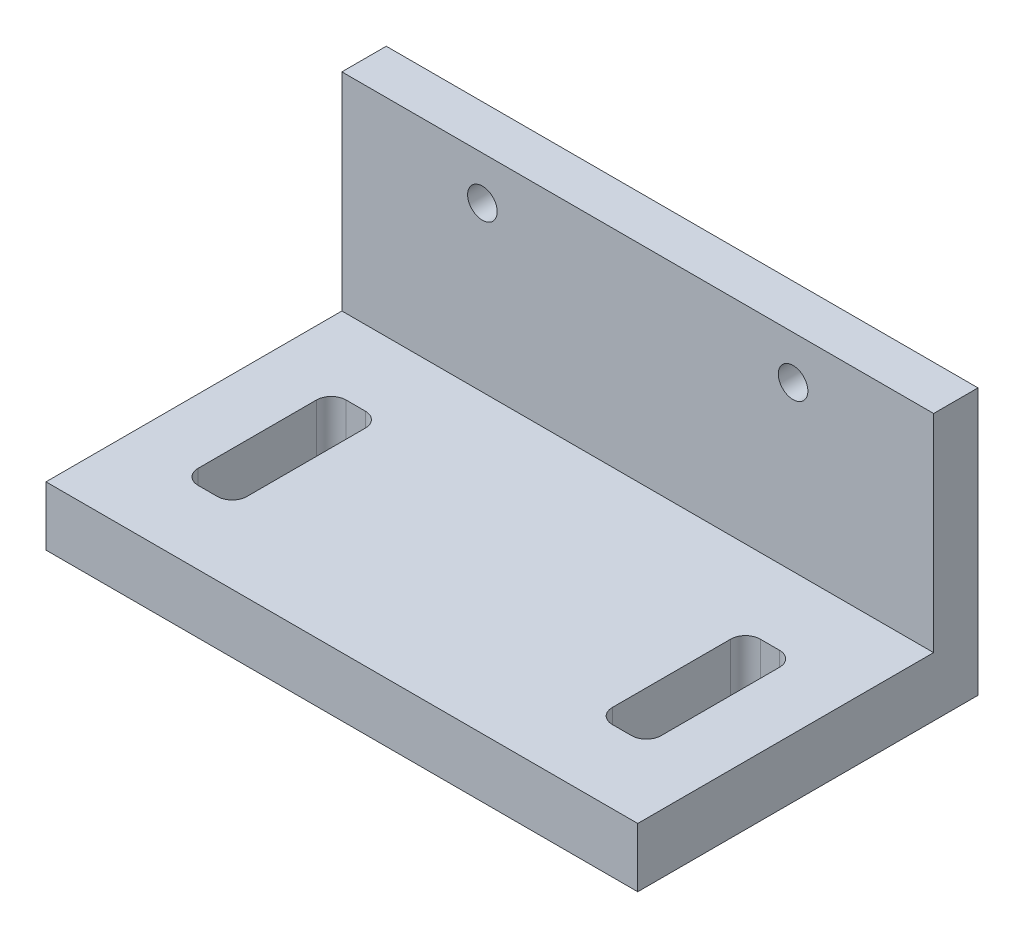
SolidWorks part; units mm, degrees
ref_plane "Front Plane" through (0, 0, 0) normal (0, 0, 1) x (1, 0, 0)
ref_plane "Top Plane" through (0, 0, 0) normal (0, 1, 0) x (1, 0, 0)
ref_plane "Right Plane" through (0, 0, 0) normal (1, 0, 0) x (0, 0, -1)
sketch "Sketch1" plane through (0, 0, 0) normal (0, 1, 0) x (1, 0, 0)
  line L0 (0, 12.5338) -> (0, -16.2828) construction
  line L1 (-20, 10) -> (20, 10)
  line L2 (-20, 10) -> (-20, -10)
  line L3 (-20, -10) -> (20, -10)
  line L4 (20, 10) -> (20, -10)
  line L5 (-20, 10) -> (20, -10) construction
  line L6 (-20, -10) -> (20, 10) construction
  line L7 (13.35, 4.9319) -> (14.65, 4.9319)
  line L8 (12.35, 3.9319) -> (12.35, -4.0681)
  line L9 (13.35, -5.0681) -> (14.65, -5.0681)
  line L10 (15.65, 3.9319) -> (15.65, -4.0681)
  line L11 (12.35, 4.9319) -> (15.65, -5.0681) construction
  line L12 (12.35, -5.0681) -> (15.65, 4.9319) construction
  line L13 (-12.35, -5.0681) -> (-15.65, 4.9319) construction
  line L14 (-12.35, 4.9319) -> (-15.65, -5.0681) construction
  line L15 (20, -10) -> (-20, 10) construction
  line L16 (20, 10) -> (-20, -10) construction
  line L17 (-15.65, 3.9319) -> (-15.65, -4.0681)
  line L18 (-13.35, -5.0681) -> (-14.65, -5.0681)
  line L19 (-12.35, 3.9319) -> (-12.35, -4.0681)
  line L20 (-13.35, 4.9319) -> (-14.65, 4.9319)
  arc A0 (13.35, -5.0681) -> (12.35, -4.0681) centre (13.35, -4.0681) cw
  arc A1 (14.65, -5.0681) -> (15.65, -4.0681) centre (14.65, -4.0681) ccw
  arc A2 (15.65, 3.9319) -> (14.65, 4.9319) centre (14.65, 3.9319) ccw
  arc A3 (12.35, 3.9319) -> (13.35, 4.9319) centre (13.35, 3.9319) cw
  arc A4 (-12.35, 3.9319) -> (-13.35, 4.9319) centre (-13.35, 3.9319) ccw
  arc A5 (-15.65, 3.9319) -> (-14.65, 4.9319) centre (-14.65, 3.9319) cw
  arc A6 (-14.65, -5.0681) -> (-15.65, -4.0681) centre (-14.65, -4.0681) cw
  arc A7 (-13.35, -5.0681) -> (-12.35, -4.0681) centre (-13.35, -4.0681) ccw
  point P0 (0, 0)
  point P6 (14, -0.0681)
  point P41 (-14, -0.0681)
  dimension "D6" = 1
  dimension "D1" = 40
  dimension "D2" = 20
  dimension "D3" = 3.3
  dimension "D4" = 10
  dimension "D5" = 14
extrude "Boss-Extrude1" add sketch "Sketch1" along normal blind 4
sketch "Sketch2" plane through (0, 0, 0) normal (0, 1, 0) x (1, 0, 0)
  line L0 (20, -10) -> (20, 10) construction
  line L1 (-20, 10) -> (20, 10)
  line L2 (-20, 10) -> (-20, 13)
  line L3 (-20, 13) -> (20, 13)
  line L4 (20, 10) -> (20, 13)
  dimension "D1" = 0
  dimension "D2" = 3
extrude "Boss-Extrude2" add sketch "Sketch2" along normal blind 18
sketch "Sketch3" plane through (0, 0, -13) normal (0, 0, -1) x (-1, 0, 0)
  line L1 (0, 21.7938) -> (0, -10.9305) construction
  circle A0 centre (10.5, 15.0632) radius 1
  circle A1 centre (-10.5, 15.0632) radius 1
  dimension "D1" = 2
  dimension "D2" = 10.5
extrude "Cut-Extrude1" cut sketch "Sketch3" against normal through all
